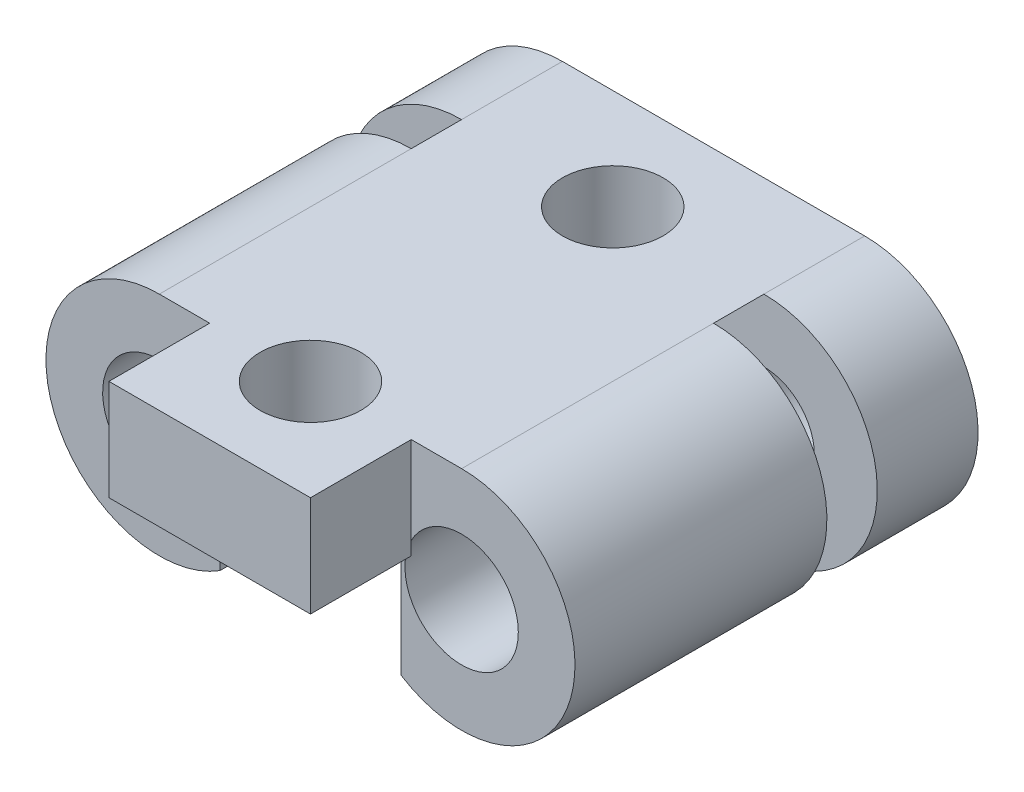
SolidWorks part; units mm, degrees
ref_plane "Front Plane" through (0, 0, 0) normal (0, 0, 1) x (1, 0, 0)
ref_plane "Top Plane" through (0, 0, 0) normal (0, 1, 0) x (1, 0, 0)
ref_plane "Right Plane" through (0, 0, 0) normal (1, 0, 0) x (0, 0, -1)
sketch "Sketch2" plane through (0, 0, 0) normal (0, 1, 0) x (1, 0, 0)
  line L0 (-4, 0) -> (4, 0) construction
  line L1 (-4, -10) -> (4, -10)
  line L2 (-4, -10) -> (-4, 10)
  line L3 (-4, 10) -> (4, 10)
  line L4 (4, -10) -> (4, 10)
  line L5 (-4, -10) -> (4, 10) construction
  line L6 (-4, 10) -> (4, -10) construction
  circle A0 centre (0, 6) radius 2
  circle A1 centre (0, -6) radius 2
  point P0 (0, 0)
  dimension "D4" = 4
  dimension "D1" = 8
  dimension "D2" = 20
  dimension "D3" = 12
extrude "Boss-Extrude2" add sketch "Sketch2" against normal blind 4
sketch "Sketch3" plane through (0, 0, -10) normal (0, 0, 1) x (1, 0, 0)
  line L0 (-4, 0) -> (4, 0) construction
  line L1 (0, 4.6733) -> (0, -6.6144) construction
  line L2 (6, 0) -> (4, 0)
  line L3 (4, 0) -> (4, -0.4689)
  line L4 (-6, 0) -> (-4, 0)
  line L5 (-4, 0) -> (-4, -0.4689)
  line L6 (-4, -4) -> (-4, 0) construction
  arc A0 (4, -0.4689) -> (6, 0) centre (6, -4.5) ccw
  circle A1 centre (6, -4.5) radius 2
  circle A2 centre (-6, -4.5) radius 2
  arc A3 (-6, 0) -> (-4, -0.4689) centre (-6, -4.5) ccw
  dimension "D1" = 4
  dimension "D2" = 2.5
  dimension "D3" = 6
extrude "Boss-Extrude3" add sketch "Sketch3" along normal blind 16
sketch "Sketch5" plane through (0, 0, 6) normal (0, 0, 1) x (1, 0, 0)
  circle A0 centre (-6, -4.5) radius 2.25
  circle A1 centre (6, -4.5) radius 2.25
  dimension "D1" = 4.5
extrude "Cut-Extrude1" cut sketch "Sketch5" against normal offset from surface (10 mm away) 6 up to face at (0, -4.9271, -10)
sketch "Sketch6" plane through (0, 0, -4) normal (0, 0, 1) x (1, 0, 0)
  circle A0 centre (6, -4.5) radius 4.5
  circle A1 centre (-6, -4.5) radius 4.5
  arc A2 (1.5279, -4) -> (6, 0) centre (6, -4.5) ccw construction
extrude "Cut-Extrude2" cut sketch "Sketch6" against normal blind 2
sketch "Sketch7" plane through (0, -4, 0) normal (0, -1, 0) x (1, 0, 0)
  circle A0 centre (0, 6) radius 3.6
  circle A1 centre (0, -6) radius 3.6
  dimension "D1" = 7.2
extrude "Cut-Extrude3" cut sketch "Sketch7" along normal through all
sketch "Sketch8" plane through (0, 0, 0) normal (0, 1, 0) x (1, 0, 0)
  circle A0 centre (0, 6) radius 2
  circle A1 centre (0, -6) radius 2
  circle A2 centre (0, -6) radius 2 construction
  circle A3 centre (0, 6) radius 2 construction
extrude "Cut-Extrude4" cut sketch "Sketch8" against normal through all
